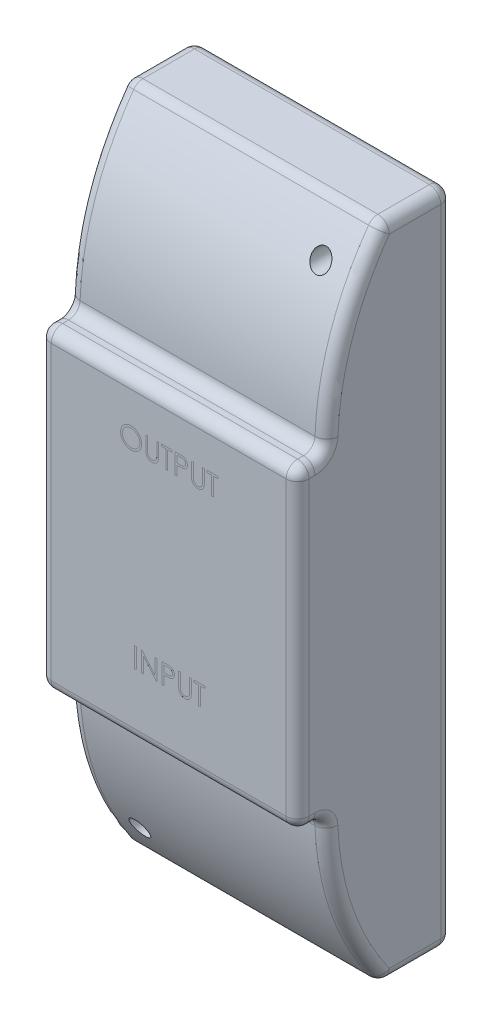
SolidWorks part; units mm, degrees
material "ABS"
ref_plane "Plan de face" through (0, 0, 0) normal (0, 0, 1) x (1, 0, 0)
ref_plane "Plan de dessus" through (0, 0, 0) normal (0, 1, 0) x (1, 0, 0)
ref_plane "Plan de droite" through (0, 0, 0) normal (1, 0, 0) x (0, 0, -1)
sketch "Esquisse1" plane through (0, 0, 0) normal (0, 0, 1) x (1, 0, 0)
  line L1 (-22.5, 57.5) -> (22.5, 57.5)
  line L2 (-22.5, 57.5) -> (-22.5, -57.5)
  line L3 (-22.5, -57.5) -> (22.5, -57.5)
  line L4 (22.5, 57.5) -> (22.5, -57.5)
  line L5 (-22.5, 57.5) -> (22.5, -57.5) construction
  line L6 (-22.5, -57.5) -> (22.5, 57.5) construction
  point P0 (0, 0)
  dimension "D1" = 115
  dimension "D2" = 45
extrude "Boss.-Extru.1" add sketch "Esquisse1" along normal blind 27
sketch "Esquisse2" plane through (-22.5, 0, 0) normal (-1, 0, 0) x (0, 0, 1)
  line L0 (30.8718, 27.5) -> (22, 27.5)
  line L1 (27, 57.5) -> (0, 57.5) construction
  line L2 (12, 57.5) -> (30.8718, 57.5)
  line L3 (30.8718, 57.5) -> (30.8718, 27.5)
  line L4 (27, 57.5) -> (27, -57.5) construction
  arc A0 (22, 27.5) -> (12, 57.5) centre (-28, 27.5) ccw
  dimension "D1" = 5
  dimension "D3" = 50
  dimension "D2" = 15
  dimension "D4" = 30
extrude "Enlèv. mat.-Extru.1" cut sketch "Esquisse2" against normal through all
mirror "Symétrie1" about plane through (0, 0, 0) normal (0, 1, 0) of "Enlèv. mat.-Extru.1"
fillet "Congé1" radius 2 24 edges at (22.5, -27.5, 24.5) (22.5, 27.5, 24.5) (22.5, 0, 0) (0, 57.5, 0) (22.5, 57.5, 6) (0, 57.5, 12) (22.5, 43.3114, 19.4342) (0, 27.5, 22) (22.5, -57.5, 6) (0, -57.5, 0) (-22.5, -57.5, 6) (-22.5, 0, 0) (-22.5, 57.5, 6) (-22.5, 43.3114, 19.4342) (-22.5, 27.5, 24.5) (-22.5, -27.5, 24.5) (0, -27.5, 22) (22.5, -43.3114, 19.4342) (0, -57.5, 12) (-22.5, -43.3114, 19.4342) (0, 27.5, 27) (22.5, 0, 27) (0, -27.5, 27) (-22.5, 0, 27)
sketch "Sketch1" plane through (0, 0, 27) normal (0, 0, 1) x (1, 0, 0)
  line L0 (-12.8168, 16.4216) -> (12.8168, 16.4216) construction
  line L1 (-12.8168, -16.4216) -> (12.8168, -16.4216) construction
  line L2 (0, 16.4216) -> (0, -16.4216) construction
  text T0 "OUTPUT"
  text T1 "INPUT"
extrude "Cut-Extrude1" cut sketch "Sketch1" against normal blind 0.001
sketch "Sketch2" plane through (0, 0, 0) normal (0, 0, -1) x (-1, 0, 0)
  line L0 (-20.5, 57.5) -> (20.5, 57.5) construction
  line L1 (-22.5, -55.5) -> (-22.5, 55.5) construction
  line L2 (20.5, -57.5) -> (-20.5, -57.5) construction
  line L3 (22.5, 55.5) -> (22.5, -55.5) construction
  circle A0 centre (-15.8, 50.8) radius 1.7
  circle A1 centre (15.8, -50.8) radius 1.7
  point P14 (16.554, -50.0657)
  point P15 (14.854, -48.3657)
  point P16 (14.854, -51.7657)
  dimension "D1" = 3.4
  dimension "D3" = 5
  dimension "D4" = 3.4
  dimension "D5" = 5
  dimension "D6" = 5
  dimension "D2" = 5
extrude "Cut-Extrude2" cut sketch "Sketch2" against normal up to next
